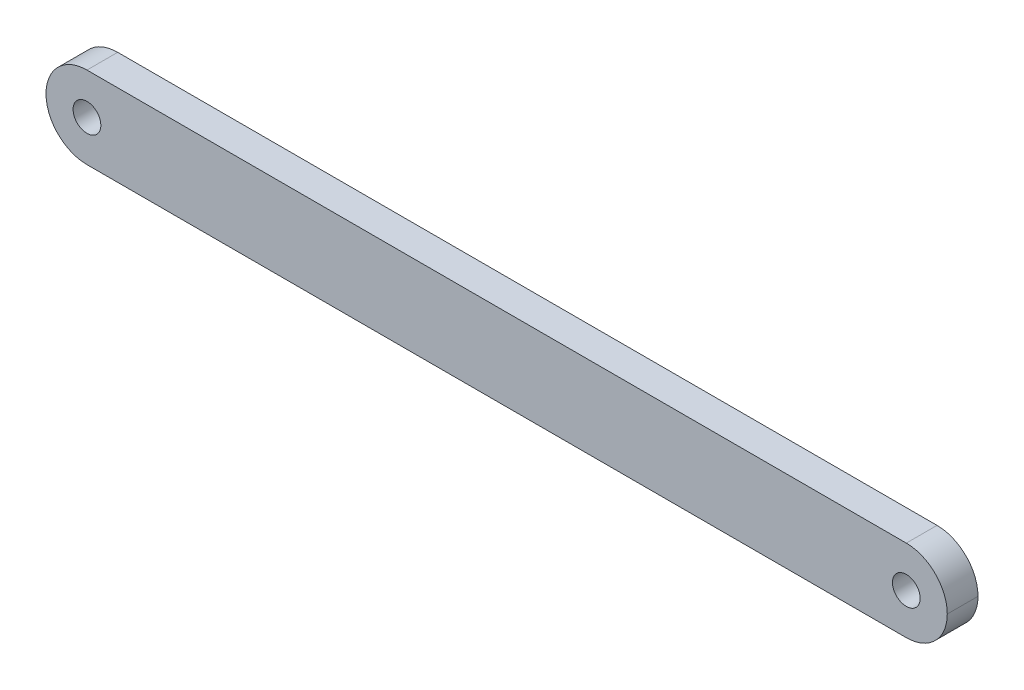
SolidWorks part; units mm, degrees
ref_plane "前视基准面" through (0, 0, 0) normal (0, 0, 1) x (1, 0, 0)
ref_plane "上视基准面" through (0, 0, 0) normal (0, 1, 0) x (1, 0, 0)
ref_plane "右视基准面" through (0, 0, 0) normal (1, 0, 0) x (0, 0, -1)
ref_plane "基准面4" through (0, 0, 0) normal (0, 0, -1) x (-1, 0, 0)
sketch "草图1" plane through (0, 0, 0) normal (0, 0, -1) x (-1, 0, 0)
  line L0 (-55.8602, 0) -> (24.1383, 0)
  line L1 (24.1383, 7.999) -> (-55.8602, 7.999)
  arc A0 (-55.8602, 7.999) -> (-59.8602, 4) centre (-55.8602, 3.999) ccw
  arc A1 (-59.8602, 4) -> (-55.8602, 0) centre (-55.8602, 4) ccw
  arc A2 (24.1383, 0) -> (28.1383, 3.999) centre (24.1383, 4) ccw
  arc A3 (28.1383, 3.999) -> (24.1383, 7.999) centre (24.1383, 3.999) ccw
  circle A4 centre (24.1388, 3.9985) radius 1.354
  circle A5 centre (-55.8597, 3.9995) radius 1.354
extrude "凸台-拉伸1" add sketch "草图1" against normal blind 3
